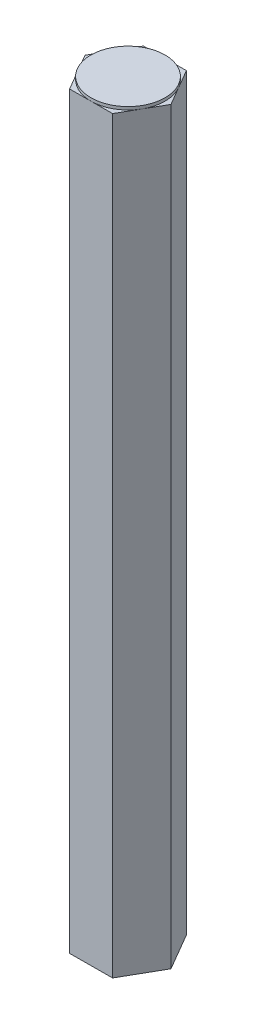
SolidWorks part; units mm, degrees
material "1060 Alloy"
ref_plane "Front Plane" through (0, 0, 0) normal (0, 0, 1) x (1, 0, 0)
ref_plane "Top Plane" through (0, 0, 0) normal (0, 1, 0) x (1, 0, 0)
ref_plane "Right Plane" through (0, 0, 0) normal (1, 0, 0) x (0, 0, -1)
sketch "Sketch1" plane through (0, 0, 0) normal (0, 1, 0) x (1, 0, 0)
  line L1 (1.8204, 3.1823) -> (-1.8458, 3.1677)
  line L2 (-1.8458, 3.1677) -> (-3.6661, -0.0146)
  line L3 (-3.6661, -0.0146) -> (-1.8204, -3.1823)
  line L4 (-1.8204, -3.1823) -> (1.8458, -3.1677)
  line L5 (1.8458, -3.1677) -> (3.6661, 0.0146)
  line L6 (3.6661, 0.0146) -> (1.8204, 3.1823)
  circle A0 centre (0, 0) radius 3.175 construction
  dimension "D1" = 6.35
extrude "Boss-Extrude1" add sketch "Sketch1" along normal blind 64.135
sketch "Sketch2" plane through (0, 64.135, 0) normal (0, 1, 0) x (1, 0, 0)
  circle A0 centre (0, 0) radius 3.175
extrude "Boss-Extrude2" add sketch "Sketch2" along normal blind 0.254
